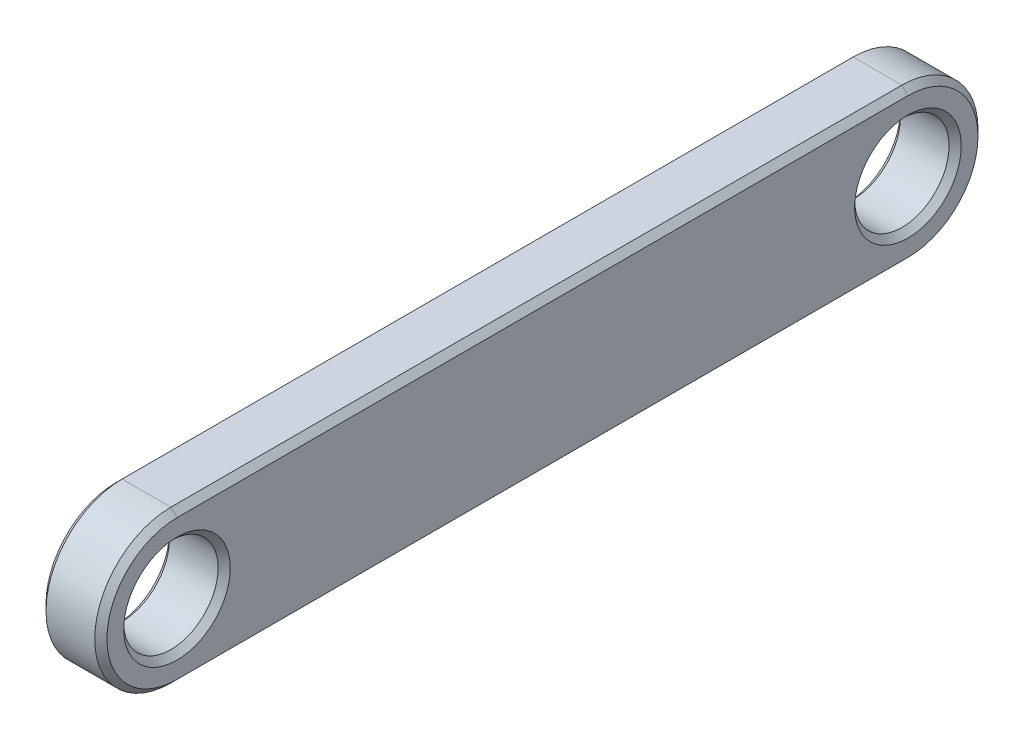
SolidWorks part; units mm, degrees
ref_plane "Front Plane" through (0, 0, 0) normal (0, 0, 1) x (1, 0, 0)
ref_plane "Top Plane" through (0, 0, 0) normal (0, 1, 0) x (1, 0, 0)
ref_plane "Right Plane" through (0, 0, 0) normal (1, 0, 0) x (0, 0, -1)
sketch "Sketch1" plane through (0, 0, 0) normal (1, 0, 0) x (0, 0, -1)
  line L0 (-12, 0) -> (12, 0) construction
  line L1 (-12, 2.5) -> (12, 2.5)
  line L2 (-12, -2.5) -> (12, -2.5)
  arc A0 (-12, 2.5) -> (-12, -2.5) centre (-12, 0) ccw
  arc A1 (12, -2.5) -> (12, 2.5) centre (12, 0) ccw
  circle A2 centre (-12, 0) radius 1.55
  circle A3 centre (12, 0) radius 1.55
  point P3 (0, 0)
  dimension "D1" = 3.1
  dimension "D2" = 3.1
  dimension "D4" = 2.5
  dimension "D3" = 24
extrude "Boss-Extrude1" add sketch "Sketch1" along normal blind 2
chamfer "Chamfer1" distance 0.2 angle 45 12 edges at (0, 0, -13.55) (0, 0, 10.45) (0, -2.5, 0) (0, 0, -14.5) (0, 2.5, 0) (0, 0, 14.5) (2, 0, -13.55) (2, 2.5, 0) (2, 0, -14.5) (2, -2.5, 0) (2, 0, 14.5) (2, 0, 10.45)
